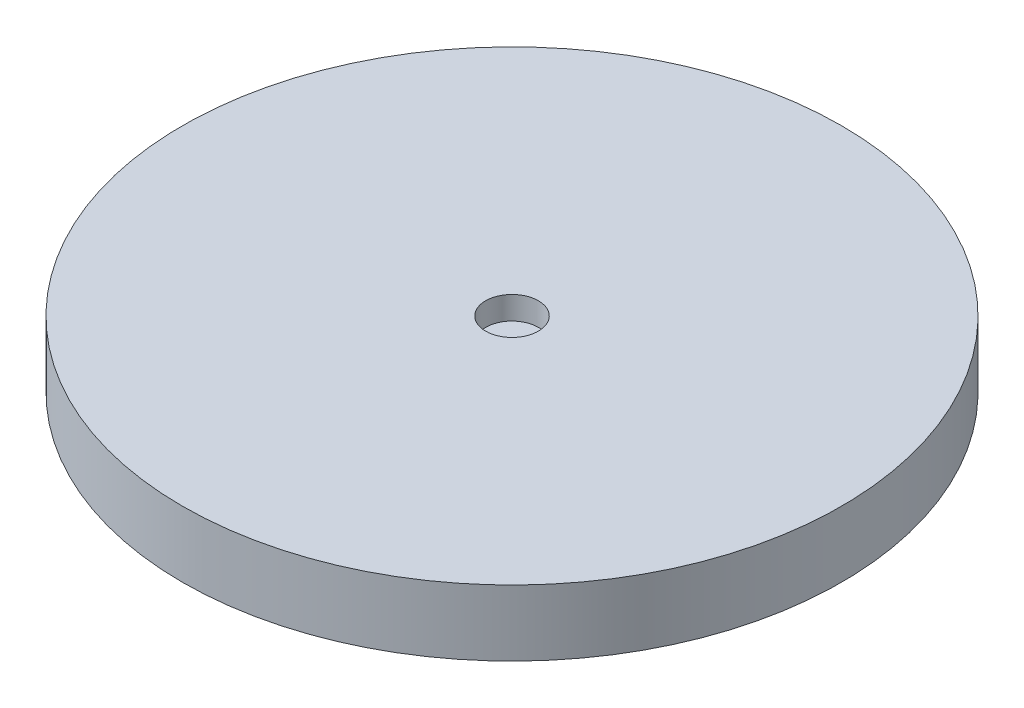
SolidWorks part; units mm, degrees
ref_plane "Front Plane" through (0, 0, 0) normal (0, 0, 1) x (1, 0, 0)
ref_plane "Top Plane" through (0, 0, 0) normal (0, 1, 0) x (1, 0, 0)
ref_plane "Right Plane" through (0, 0, 0) normal (1, 0, 0) x (0, 0, -1)
sketch "Sketch1" plane through (0, 0, 0) normal (0, 1, 0) x (1, 0, 0)
  circle A0 centre (0, 0) radius 50
  dimension "D1" = 100
extrude "Boss-Extrude1" add sketch "Sketch1" along normal blind 10
sketch "Sketch2" plane through (0, 10, 0) normal (0, 1, 0) x (1, 0, 0)
  circle A0 centre (0, 0) radius 4
  dimension "D1" = 8
extrude "Cut-Extrude1" cut sketch "Sketch2" against normal blind 3.5
